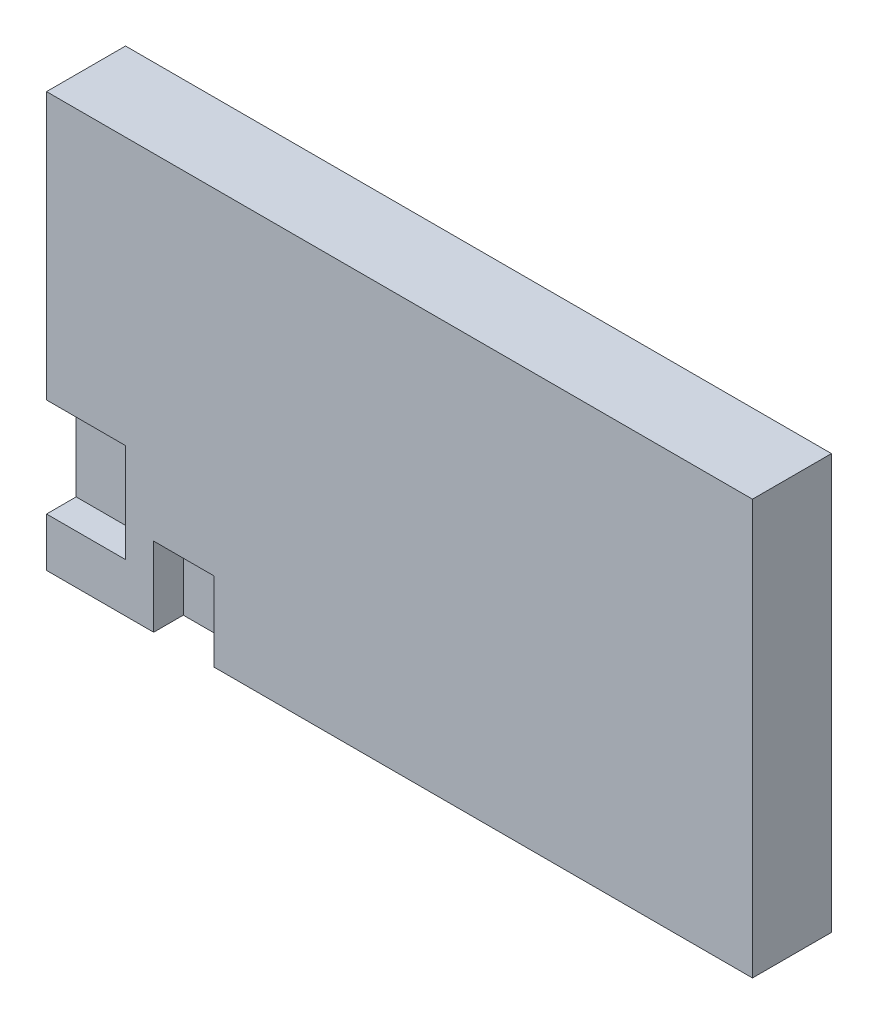
SolidWorks part; units mm, degrees
ref_plane "前基準面" through (0, 0, 0) normal (0, 0, 1) x (1, 0, 0)
ref_plane "上基準面" through (0, 0, 0) normal (0, 1, 0) x (1, 0, 0)
ref_plane "右基準面" through (0, 0, 0) normal (1, 0, 0) x (0, 0, -1)
sketch "草圖1" plane through (0, 0, 0) normal (0, 0, 1) x (1, 0, 0)
  line L1 (-65.9064, 28.838) -> (77.0936, 28.838)
  line L2 (-65.9064, 28.838) -> (-65.9064, -55.162)
  line L3 (-65.9064, -55.162) -> (77.0936, -55.162)
  line L4 (77.0936, 28.838) -> (77.0936, -55.162)
  dimension "D1" = 143
  dimension "D2" = 84
extrude "填料-伸長1" add sketch "草圖1" along normal blind 16
sketch "草圖2" plane through (0, 0, 16) normal (0, 0, 1) x (1, 0, 0)
  line L0 (-65.9064, 28.838) -> (-65.9064, -55.162) construction
  line L1 (-65.9064, -25.262) -> (-49.9064, -25.262)
  line L2 (-65.9064, -25.262) -> (-65.9064, -45.262)
  line L3 (-65.9064, -45.262) -> (-49.9064, -45.262)
  line L4 (-49.9064, -25.262) -> (-49.9064, -45.262)
  line L5 (-65.9064, -55.162) -> (77.0936, -55.162) construction
  line L6 (-44.2064, -39.162) -> (-32.0064, -39.162)
  line L7 (-44.2064, -39.162) -> (-44.2064, -55.162)
  line L8 (-44.2064, -55.162) -> (-32.0064, -55.162)
  line L9 (-32.0064, -39.162) -> (-32.0064, -55.162)
  line L10 (77.0936, -55.162) -> (77.0936, 28.838) construction
  line L11 (77.0936, 28.838) -> (-65.9064, 28.838) construction
  dimension "D1" = 21.7
  dimension "D2" = 109.1
  dimension "D3" = 9.9
  dimension "D4" = 54.1
  dimension "D5" = 16
  dimension "D6" = 16
extrude "除料-伸長1" cut sketch "草圖2" against normal blind 6
